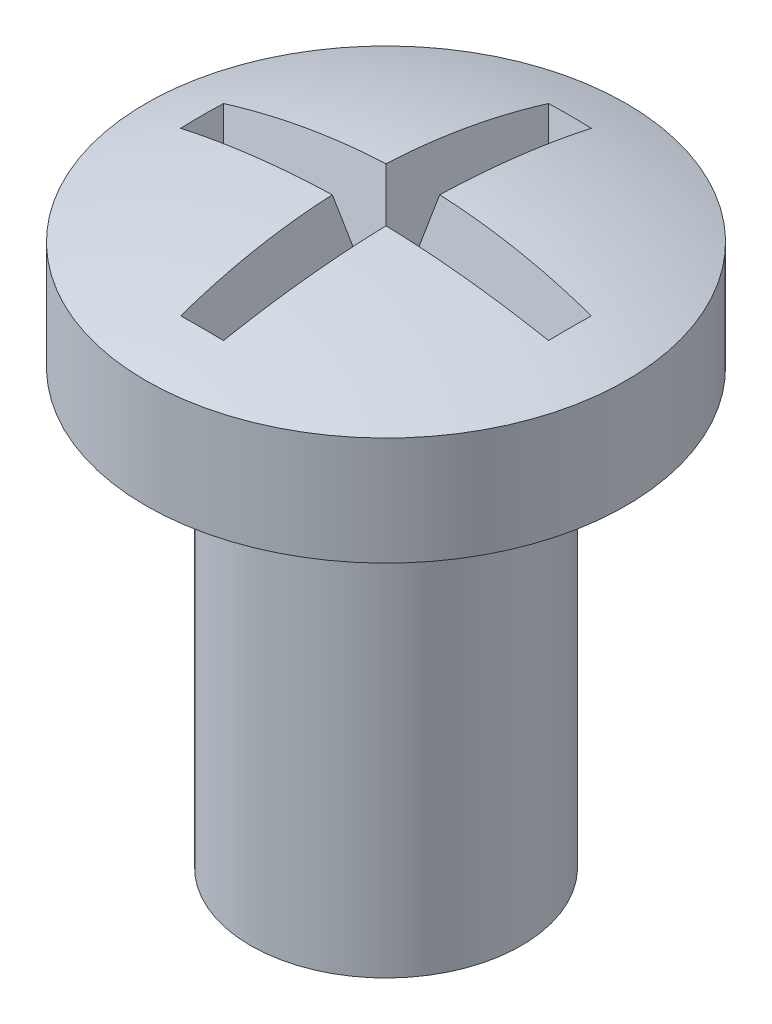
SolidWorks part; units mm, degrees
ref_plane "Спереди" through (0, 0, 0) normal (0, 0, 1) x (1, 0, 0)
ref_plane "Сверху" through (0, 0, 0) normal (0, 1, 0) x (1, 0, 0)
ref_plane "Справа" through (0, 0, 0) normal (1, 0, 0) x (0, 0, -1)
sketch "Эскиз1" plane through (0, 0, 0) normal (0, 0, 1) x (1, 0, 0)
  line L0 (0, 0) -> (-1.25, 0)
  line L1 (-1.25, 0) -> (-1.25, 4)
  line L4 (0, 5.3866) -> (0, 0)
  line L5 (-1.25, 4) -> (-2.2165, 4)
  line L7 (-2.2165, 4) -> (-2.2165, 5)
  arc A1 (-2.2165, 5) -> (0, 5.3866) centre (0, -1.1606) cw
  point P6 (0, 0)
  point P10 (0, 5.8115)
  point P11 (0, 6.205)
  point P12 (0, 0)
  point P13 (0, 5.3947)
  point P14 (0, 5.2578)
  dimension "D1" = 4
  dimension "D2" = 1
  dimension "D3" = 2.25
  dimension "D4" = 1.25
revolve "Повернуть1" add sketch "Эскиз1" angle 360 about L4
ref_plane "Плоскость1" through (0, 5.3866, 0) normal (0, 1, 0) x (1, 0, 0)
sketch "Эскиз3" plane through (0, 5.3866, 0) normal (0, 1, 0) x (1, 0, 0)
  line L0 (-0.25, 0.25) -> (-1.75, 0.25)
  line L1 (-0.25, -1.75) -> (0.25, -1.75)
  line L2 (-0.25, -1.75) -> (-0.25, -0.25)
  line L3 (-0.25, 1.75) -> (0.25, 1.75)
  line L4 (0.25, -1.75) -> (0.25, -0.25)
  line L5 (-0.25, -1.75) -> (0.25, 1.75) construction
  line L6 (-0.25, 1.75) -> (0.25, -1.75) construction
  line L7 (1.75, -0.25) -> (0.25, -0.25)
  line L8 (1.75, -0.25) -> (1.75, 0.25)
  line L9 (1.75, 0.25) -> (0.25, 0.25)
  line L10 (-1.75, -0.25) -> (-1.75, 0.25)
  line L11 (1.75, -0.25) -> (-1.75, 0.25) construction
  line L12 (1.75, 0.25) -> (-1.75, -0.25) construction
  line L13 (0.25, 0.25) -> (0.25, 1.75)
  line L14 (-0.25, -0.25) -> (-1.75, -0.25)
  line L15 (-0.25, 0.25) -> (-0.25, 1.75)
  point P0 (0, 0)
  point P6 (0, 0)
  dimension "D1" = 3.5
  dimension "D2" = 0.5
extrude "Вырез-Вытянуть2" cut sketch "Эскиз3" against normal blind 0.9 draft 13
